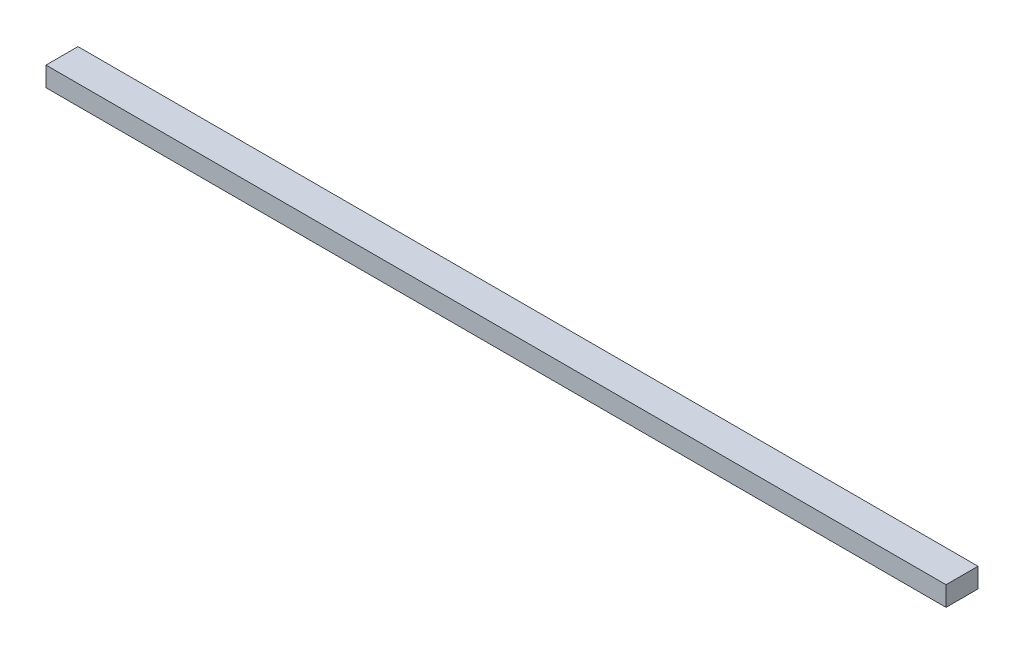
SolidWorks part; units mm, degrees
material "AISI 304"
ref_plane "Plano frontal" through (0, 0, 0) normal (0, 0, 1) x (1, 0, 0)
ref_plane "Plano superior" through (0, 0, 0) normal (0, 1, 0) x (1, 0, 0)
ref_plane "Plano direito" through (0, 0, 0) normal (1, 0, 0) x (0, 0, -1)
sketch "Esboço1" plane through (0, 0, 0) normal (1, 0, 0) x (0, 0, -1)
  line L1 (-3.25, -2) -> (3.25, -2)
  line L2 (-3.25, -2) -> (-3.25, 2)
  line L3 (-3.25, 2) -> (3.25, 2)
  line L4 (3.25, -2) -> (3.25, 2)
  line L5 (-3.25, -2) -> (3.25, 2) construction
  line L6 (-3.25, 2) -> (3.25, -2) construction
  point P0 (0, 0)
  dimension "D1" = 4
  dimension "D2" = 6.5
extrude "Ressalto-extrusão1" add sketch "Esboço1" along normal blind 183
